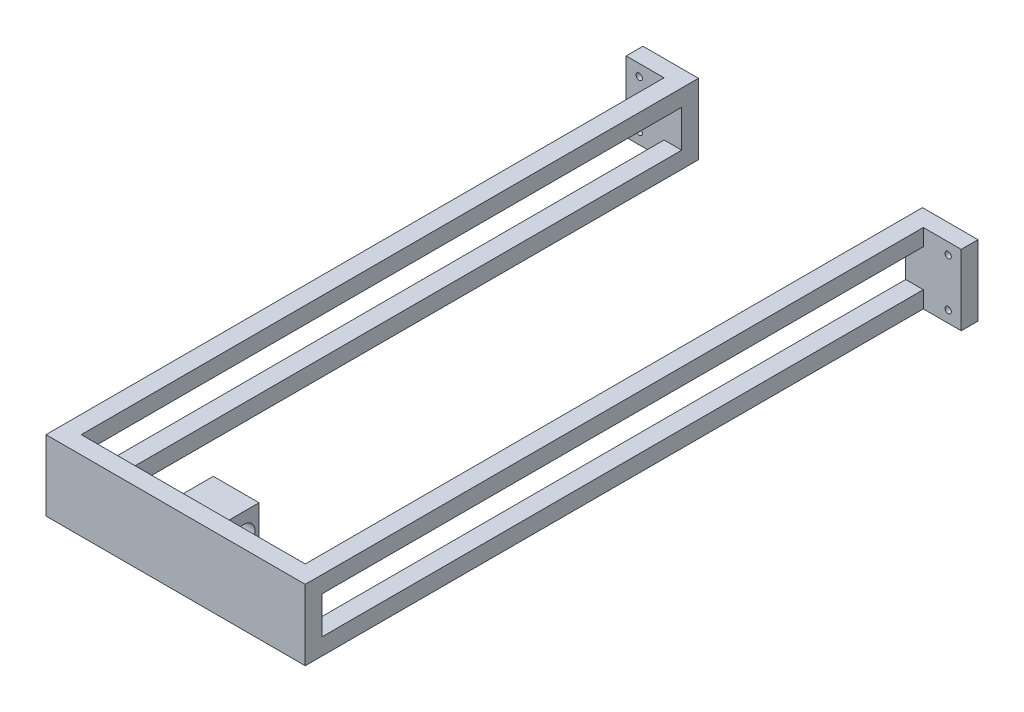
SolidWorks part; units mm, degrees
ref_plane "Front Plane" through (0, 0, 0) normal (0, 0, 1) x (1, 0, 0)
ref_plane "Top Plane" through (0, 0, 0) normal (0, 1, 0) x (1, 0, 0)
ref_plane "Right Plane" through (0, 0, 0) normal (1, 0, 0) x (0, 0, -1)
sketch "Sketch2" plane through (0, 0, 0) normal (0, 0, 1) x (1, 0, 0)
  line L1 (-55.626, 8.5699) -> (55.626, 8.5699)
  line L2 (-55.626, 8.5699) -> (-55.626, -8.5699)
  line L3 (-55.626, -8.5699) -> (55.626, -8.5699)
  line L4 (55.626, 8.5699) -> (55.626, -8.5699)
  line L5 (-55.626, 8.5699) -> (55.626, -8.5699) construction
  line L6 (-55.626, -8.5699) -> (55.626, 8.5699) construction
  line L7 (-60.325, 12.7) -> (60.325, 12.7)
  line L8 (-60.325, 12.7) -> (-60.325, -12.7)
  line L9 (-60.325, -12.7) -> (60.325, -12.7)
  line L10 (60.325, 12.7) -> (60.325, -12.7)
  line L11 (-60.325, 12.7) -> (60.325, -12.7) construction
  line L12 (-60.325, -12.7) -> (60.325, 12.7) construction
  point P0 (0, 0)
  point P6 (0, 0)
  dimension "D1" = 111.252
  dimension "D2" = 17.1398
  dimension "D3" = 25.4
  dimension "D4" = 120.65
extrude "Boss-Extrude2" add sketch "Sketch2" along normal blind 228.6 contours L7 L10 L9 L8
sketch "Sketch3" plane through (0, -12.7, 0) normal (0, -1, 0) x (1, 0, 0)
  line L0 (-46.675, 6.0398) -> (-60.325, 6.0398)
  line L2 (-40.325, 6.0398) -> (-40.325, 222.25)
  line L3 (-40.325, 222.25) -> (40.325, 222.25)
  line L4 (40.325, 222.25) -> (40.325, 6.0398)
  line L5 (-60.325, 228.6) -> (-60.325, 0) construction
  line L7 (-60.325, 228.6) -> (60.325, 228.6) construction
  line L8 (-46.675, 6.0398) -> (-46.675, 228.6)
  line L9 (-46.675, 228.6) -> (46.675, 228.6)
  line L10 (46.675, 228.6) -> (46.675, 6.0398)
  line L11 (-40.325, 6.0398) -> (-40.325, 0)
  line L12 (40.325, 6.0398) -> (40.325, 0)
  line L13 (-60.325, 6.0398) -> (-60.325, 0)
  line L14 (-60.325, 0) -> (-40.325, 0)
  line L15 (46.675, 6.0398) -> (60.325, 6.0398)
  line L16 (60.325, 228.6) -> (60.325, 0) construction
  line L17 (60.325, 6.0398) -> (60.325, 0)
  line L18 (60.325, 0) -> (40.325, 0)
  point P18 (-46.675, 6.0398)
  point P20 (46.675, 6.0398)
  line M2 (-60.325, 0) -> (60.325, 0)
  line M3 (60.325, 0) -> (60.325, 228.6)
  line M4 (60.325, 228.6) -> (-60.325, 228.6)
  line M5 (-60.325, 228.6) -> (-60.325, 0)
  dimension "D3" = 6.35
  dimension "D4" = 6.35
  dimension "D5" = 6.35
hole_wizard "#4-40 Tapped Hole2" positions "Sketch6" profile "Sketch7" tap size "#4-40" standard "ANSI Inch" end condition through all
sketch "Sketch6" plane through (0, 0, 228.6) normal (0, 0, 1) x (1, 0, 0)
  point P0 (-55.626, 8.5699)
  point P3 (-55.626, -8.5699)
  point P6 (55.626, 8.5699)
  point P9 (55.626, -8.5699)
cosmetic thread "Hole Thread5" parameters "D2"=2.8448
cosmetic thread "Hole Thread6" parameters "D2"=2.8448
cosmetic thread "Hole Thread7" parameters "D2"=2.8448
cosmetic thread "Hole Thread8" parameters "D2"=2.8448
sketch "Sketch7" plane through (-55.626, 8.5699, 228.6) normal (1, 0, 0) x (0, -1, 0)
  line L0 (0, 0) -> (0, 228.6)
  line L1 (0, 228.6) -> (1.1303, 228.6)
  line L2 (1.1303, 228.6) -> (1.1303, 0)
  line L5 (1.1303, 0) -> (0, 0)
  line L11 (0, -6.35) -> (0, 107.95) construction
  dimension "Thru Tap Drill Dia." = 2.2606
  dimension "Thru Tap Drill Depth" = 228.6
extrude "Cut-Extrude2" cut sketch "Sketch3" against normal blind 228.6 contours L12 L4 L3 L2 L11 M2 | L0 L8 M4 M5 | L10 L15 M3 M4
sketch "Sketch9" plane through (-46.675, 0, 0) normal (-1, 0, 0) x (0, 0, 1)
  line L0 (6.0398, 12.7) -> (6.0398, -12.7) construction
  line L1 (6.0398, 6.7) -> (222.6, 6.7)
  line L2 (6.0398, 6.7) -> (6.0398, -6.7)
  line L3 (6.0398, -6.7) -> (222.6, -6.7)
  line L4 (222.6, 6.7) -> (222.6, -6.7)
  line L5 (228.6, 12.7) -> (6.0398, 12.7) construction
  line L6 (6.0398, -12.7) -> (228.6, -12.7) construction
  line L7 (228.6, 12.7) -> (228.6, -12.7) construction
  dimension "D1" = 6
  dimension "D2" = 6
  dimension "D3" = 6
extrude "Cut-Extrude3" cut sketch "Sketch9" against normal blind 228.6
ref_plane "Plane1" through (-40.325, -12.7, 222.25) normal (1, 0, 0) x (0, 0, -1)
sketch "Sketch12" plane through (0, 0, 222.6) normal (0, 0, -1) x (-1, 0, 0)
  line L1 (-8.2396, 8.0197) -> (8.2396, 8.0197)
  line L2 (-8.2396, 8.0197) -> (-8.2396, -8.0197)
  line L3 (-8.2396, -8.0197) -> (8.2396, -8.0197)
  line L4 (8.2396, 8.0197) -> (8.2396, -8.0197)
  line L5 (-8.2396, 8.0197) -> (8.2396, -8.0197) construction
  line L6 (-8.2396, -8.0197) -> (8.2396, 8.0197) construction
  point P0 (0, 0)
  point P6 (0, 0)
extrude "Boss-Extrude4" add sketch "Sketch12" along normal blind 15.81
sketch "Sketch13" plane through (-8.2396, 0, 0) normal (-1, 0, 0) x (0, 0, 1)
  circle A0 centre (212.3277, 0) radius 4.064
  point P2 (212.3277, 0)
  dimension "D1" = 8.128
extrude "Cut-Extrude4" cut sketch "Sketch13" against normal blind 21.81
